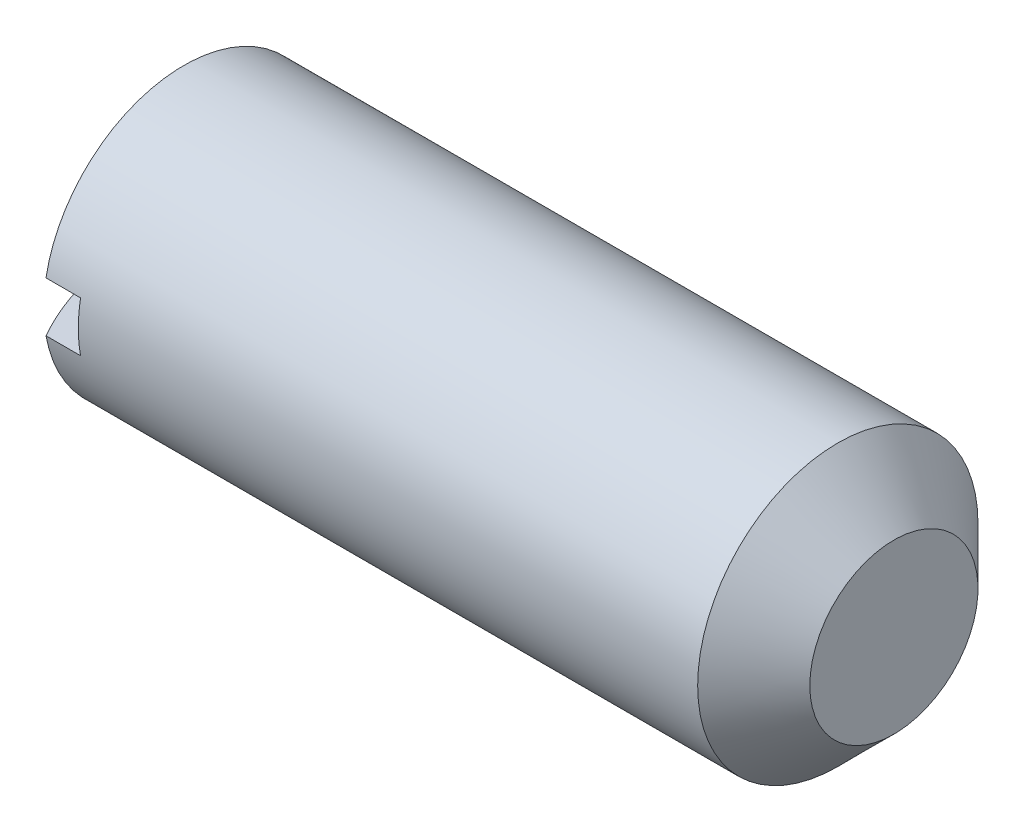
SolidWorks part; units mm, degrees
revolve "BaseBody" add sketch "BodySke" angle 360 about L5
sketch "BodySke" plane through (0, 0, 0) normal (0, 0, 1) x (1, 0, 0)
  line L0 (2.5522, -9.525) -> (47.1574, -9.525) construction
  line L1 (50.8, 0) -> (50.8, 5.715)
  line L2 (2.5522, 9.525) -> (46.99, 9.525)
  line L3 (50.8, 5.715) -> (46.99, 9.525)
  line L4 (50.8, 0) -> (0, 0)
  line L5 (-12.7, 0) -> (88.9, 0) construction
  line L6 (50.8, 5.715) -> (50.8, 19.05) construction
  line L7 (50.8, -5.715) -> (46.99, -9.525) construction
  line L8 (2.0066, 12.7) -> (2.0066, -3.175) construction
  arc A1 (2.5522, 9.525) -> (0, 0) centre (19.05, 0) ccw
  dimension "Crown_radius" = 19.05
  dimension "Diameter" = 19.05
  dimension "Nose_ch_ang" = 45
  dimension "Length" = 50.8
  dimension "Flat_dia" = 11.43
  dimension "Advance" = 2.0066
cosmetic thread "ThreadCosmetic" [suppressed] parameters "Thread_minor"=16.0249
extrude "Slot" cut sketch "Sketch2" along normal blind 4.9022
sketch "Sketch2" plane through (0, 0, 0) normal (1, 0, 0) x (0, 0, -1)
  line L1 (9.525, -1.7018) -> (-9.525, -1.7018)
  line L2 (9.525, -1.7018) -> (9.525, 1.7018)
  line L3 (9.525, 1.7018) -> (-9.525, 1.7018)
  line L4 (-9.525, -1.7018) -> (-9.525, 1.7018)
  dimension "D1" = 19.05
  dimension "Slot_width" = 3.4036
  dimension "D3" = 9.525
  dimension "D2" = 1.7018
ref_plane "Plane1" through (0, 0, 0) normal (0, 0, 1) x (1, 0, 0)
ref_plane "Plane2" through (0, 0, 0) normal (0, 1, 0) x (1, 0, 0)
ref_plane "Plane3" through (0, 0, 0) normal (1, 0, 0) x (0, 0, -1)
sketch "ThdSchSke" plane through (0, 0, 0) normal (0, 0, 1) x (1, 0, 0)
  line L0 (2.5522, -8.0124) -> (1.4931, -9.525)
  line L1 (2.5522, -8.0124) -> (3.6113, -9.525)
  line L2 (3.6113, -9.525) -> (3.6113, -11.9063)
  line L3 (-3.175, 0) -> (5.1513, 0) construction
  line L4 (2.5522, -9.525) -> (2.5522, -1.7018) construction
  line L5 (3.6113, -11.9063) -> (1.4931, -11.9063)
  line L6 (1.4931, -11.9063) -> (1.4931, -9.525)
  dimension "Diameter" = 19.05
  dimension "Thread_minor" = 16.0249
revolve "ThreadSchematic" [suppressed] cut sketch "ThdSchSke" angle 360 about L3
pattern_linear "ThdSchPat" [suppressed]
equation "\"D1@Sketch2\" = \"Diameter@BodySke\""
equation "\"D3@Sketch2\" = \"D1@Sketch2\" / 2"
equation "\"D2@Sketch2\" = \"Slot_width@Sketch2\" / 2"
equation "\"Thread_minor@ThdSchSke\" = \"Thread_minor@ThreadCosmetic\""
equation "\"Diameter@ThdSchSke\" = \"Diameter@BodySke\""
equation "\"Overcut@ThdSchSke\" = \"Diameter@BodySke\" * 1.25"
equation "\"Num_threads@ThdSchPat\" = int ( ( \"Length@BodySke\" - ( \"Crown_radius@BodySke\" - sqr ( ( \"Crown_radius@BodySke\" * \"Crown_radius@BodySke\" ) - ( ( \"Diameter@BodySke\" * 0.5 ) * ( \"Diameter@BodySke\" * 0.5 ) ) ) ) - ( ( ( \"Diameter@BodySke\" - \"Flat_dia@BodySke\" ) * 0.5 ) * tan( \"Nose_ch_ang@BodySke\" * 0.017453292 ) ) ) / \"Advance@BodySke\" + 0.999 )  + 1"
equation "\"Advance@ThdSchPat\" = ( \"Length@BodySke\" - ( \"Crown_radius@BodySke\" - sqr ( ( \"Crown_radius@BodySke\" * \"Crown_radius@BodySke\" ) - ( ( \"Diameter@BodySke\" * 0.5 ) * ( \"Diameter@BodySke\" * 0.5 ) ) ) ) - ( ( ( \"Diameter@BodySke\" - \"Flat_dia@BodySke\" ) * 0.5 ) * tan( \"Nose_ch_ang@BodySke\" * 0.017453292 ) ) ) /  (\"Num_threads@ThdSchPat\" - 1) 'relax it"
equation "' \"Num_threads@ThdSchPat\" = \"Num_threads@ThdSchPat\" - sgn( \"Num_threads@ThdSchPat\" - 1) '---chamfered tips only---"
